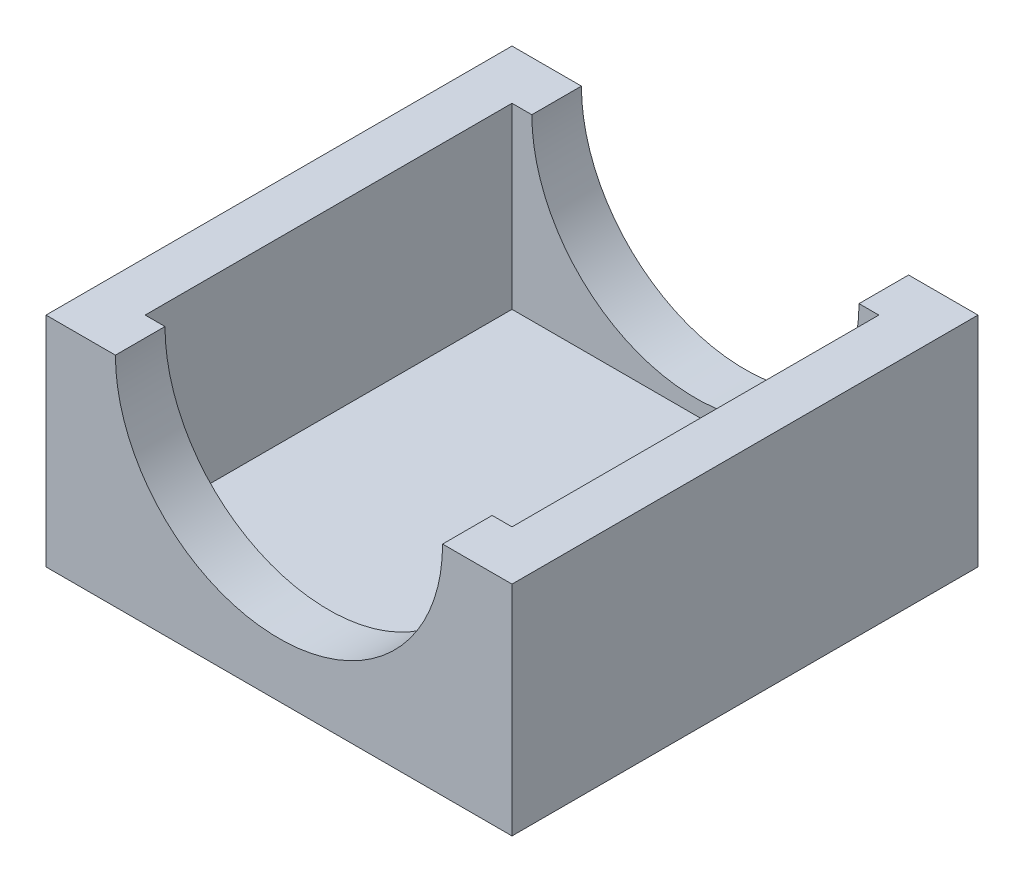
SolidWorks part; units mm, degrees
ref_plane "Front Plane" through (0, 0, 0) normal (0, 0, 1) x (1, 0, 0)
ref_plane "Top Plane" through (0, 0, 0) normal (0, 1, 0) x (1, 0, 0)
ref_plane "Right Plane" through (0, 0, 0) normal (1, 0, 0) x (0, 0, -1)
sketch "Sketch1" plane through (0, 0, 0) normal (0, 1, 0) x (1, 0, 0)
  line L1 (-37.3062, 37.3062) -> (37.3062, 37.3062)
  line L2 (-37.3062, 37.3062) -> (-37.3062, -37.3062)
  line L3 (-37.3062, -37.3062) -> (37.3063, -37.3062)
  line L4 (37.3062, 37.3062) -> (37.3063, -37.3062)
  line L5 (-37.3062, 37.3062) -> (37.3063, -37.3062) construction
  line L6 (-37.3062, -37.3062) -> (37.3062, 37.3062) construction
  point P0 (0, 0)
  dimension "D1" = 74.6125
  dimension "D2" = 74.6125
extrude "Boss-Extrude1" add sketch "Sketch1" along normal blind 34.925
sketch "Sketch2" plane through (0, 0, 37.3062) normal (0, 0, 1) x (1, 0, 0)
  line L0 (-37.3062, 34.925) -> (37.3063, 34.925) construction
  circle A0 centre (0, 34.925) radius 26.1938
extrude "Cut-Extrude1" cut sketch "Sketch2" against normal through all
sketch "Sketch3" plane through (0, 34.925, 0) normal (0, 1, 0) x (1, 0, 0)
  line L1 (-29.3688, 29.3687) -> (29.3687, 29.3687)
  line L2 (-29.3688, 29.3687) -> (-29.3688, -29.3687)
  line L3 (-29.3688, -29.3687) -> (29.3687, -29.3687)
  line L4 (29.3687, 29.3687) -> (29.3687, -29.3687)
  line L5 (-29.3688, 29.3687) -> (29.3687, -29.3687) construction
  line L6 (-29.3688, -29.3687) -> (29.3687, 29.3687) construction
  point P0 (0, 0)
  dimension "D1" = 58.7375
  dimension "D2" = 58.7375
extrude "Cut-Extrude2" cut sketch "Sketch3" against normal blind 28.575
